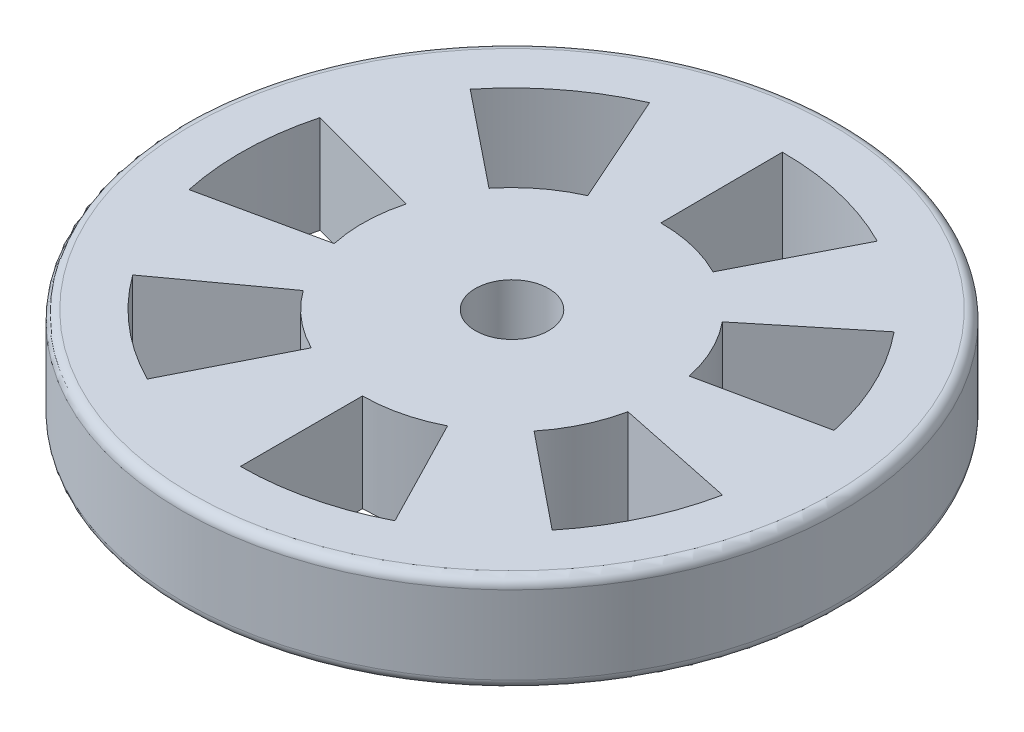
SolidWorks part; units mm, degrees
ref_plane "Front Plane" through (0, 0, 0) normal (0, 0, 1) x (1, 0, 0)
ref_plane "Top Plane" through (0, 0, 0) normal (0, 1, 0) x (1, 0, 0)
ref_plane "Right Plane" through (0, 0, 0) normal (1, 0, 0) x (0, 0, -1)
sketch "Sketch1" plane through (0, 0, 0) normal (0, 1, 0) x (1, 0, 0)
  circle A0 centre (0, 0) radius 67.5
  dimension "D1" = 135
extrude "Boss-Extrude1" add sketch "Sketch1" along normal blind 20
fillet "Fillet1" radius 2 2 edges at (0, 0, 67.5) (0, 20, 67.5)
sketch "Sketch2" plane through (0, 20, 0) normal (0, 1, 0) x (1, 0, 0)
  circle A0 centre (0, 0) radius 7.5
  dimension "D1" = 15
extrude "Cut-Extrude1" cut sketch "Sketch2" against normal through all
sketch "Sketch3" plane through (0, 0, 0) normal (0, -1, 0) x (1, 0, 0)
  line L0 (0, 30.6177) -> (0, 55.6177)
  line L1 (14.0177, 27.2204) -> (25.4634, 49.4464)
  arc A0 (14.0177, 27.2204) -> (0, 30.6177) centre (0, 0) ccw
  arc A1 (25.4634, 49.4464) -> (0, 55.6177) centre (0, 0) ccw
extrude "Cut-Extrude2" cut sketch "Sketch3" against normal through all
pattern_circular "CirPattern1" count 7 every 51 about axis through (0, 0, 0) along (0, 1, 0) of "Cut-Extrude2"
